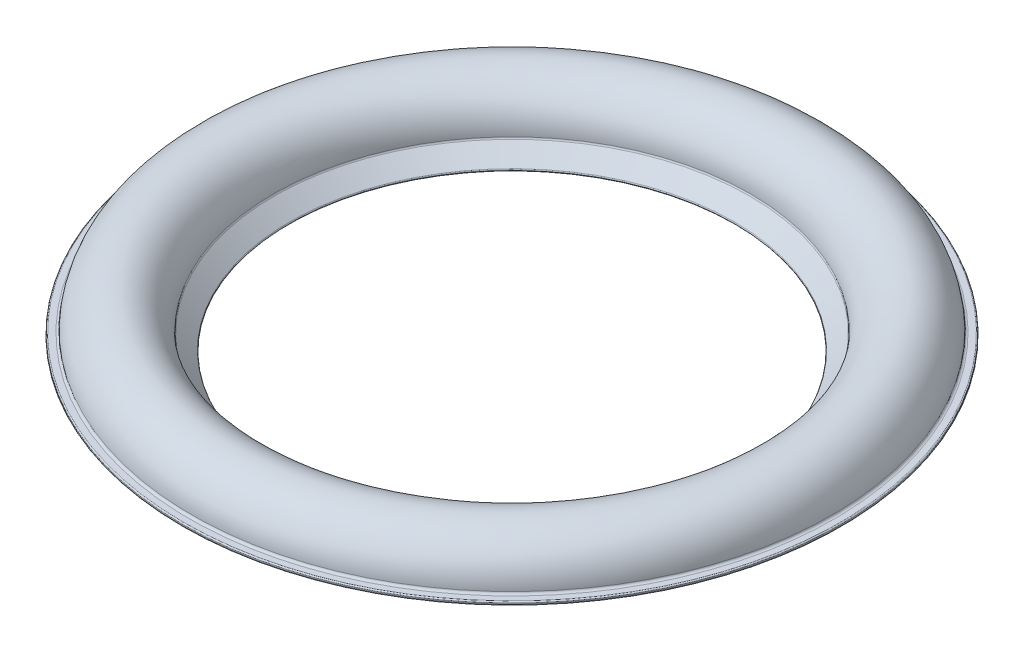
SolidWorks part; units mm, degrees
material "Бутил"
ref_plane "Спереди" through (0, 0, 0) normal (0, 0, 1) x (1, 0, 0)
ref_plane "Сверху" through (0, 0, 0) normal (0, 1, 0) x (1, 0, 0)
ref_plane "Справа" through (0, 0, 0) normal (1, 0, 0) x (0, 0, -1)
sketch "Гофра_Эскиз" plane through (0, 0, 0) normal (0, 0, 1) x (1, 0, 0)
  line L0 (95.3439, 89.637) -> (95.6877, 89.274)
  line L1 (95.363, 90.3439) -> (101.9524, 96.5865)
  line L2 (0, 0) -> (0, 145.6256) construction
  line L3 (138.2325, 96.8774) -> (140.7595, 96.8774)
  line L4 (0, 145.6256) -> (0, -32.6177) construction
  line L5 (96.3946, 89.2549) -> (102.8556, 95.3759)
  line L6 (141.2595, 96.3774) -> (141.2595, 95.8774)
  line L7 (140.7595, 95.3774) -> (136.7522, 95.3774)
  line L8 (135.7595, 95.3774) -> (135.6891, 95.3774)
  line L10 (102.8556, 95.3759) -> (103.4676, 95.9879)
  arc A0 (137.2339, 97.8234) -> (102.2644, 97.2889) centre (119.7595, 96.8774) ccw
  arc A1 (135.7526, 96.4069) -> (103.7604, 96.7057) centre (119.7595, 96.8774) ccw
  arc A2 (138.2325, 96.8774) -> (137.2339, 97.8234) centre (138.2325, 97.8774) cw
  arc A3 (102.2644, 97.2889) -> (101.9524, 96.5865) centre (101.2646, 97.3124) cw
  arc A4 (103.7604, 96.7057) -> (103.4676, 95.9879) centre (102.7605, 96.695) cw
  arc A5 (136.7522, 95.3774) -> (135.7526, 96.4069) centre (136.7522, 96.3774) cw
  arc A6 (141.2595, 95.8774) -> (140.7595, 95.3774) centre (140.7595, 95.8774) cw
  arc A7 (140.7595, 96.8774) -> (141.2595, 96.3774) centre (140.7595, 96.3774) cw
  arc A8 (95.6877, 89.274) -> (96.3946, 89.2549) centre (96.0507, 89.6179) ccw
  arc A9 (95.363, 90.3439) -> (95.3439, 89.637) centre (95.7068, 89.9809) ccw
  point P17 (137.2595, 96.8774)
  point P20 (102.2595, 96.8774)
  point P28 (141.2595, 95.3774)
  point P31 (141.2595, 96.8774)
  point P34 (96.0316, 88.9111)
  point P37 (95, 90)
  dimension "D10" = 1
  dimension "D8" = 0.5
  dimension "D1" = 95
  dimension "D2" = 10
  dimension "D3" = 35
  dimension "D4" = 4
  dimension "D5" = 90
  dimension "D6" = 1.5
  dimension "D7" = 1.5
  dimension "D9" = 9.4
revolve "Повернуть3" add sketch "Гофра_Эскиз" angle 360 about L2
